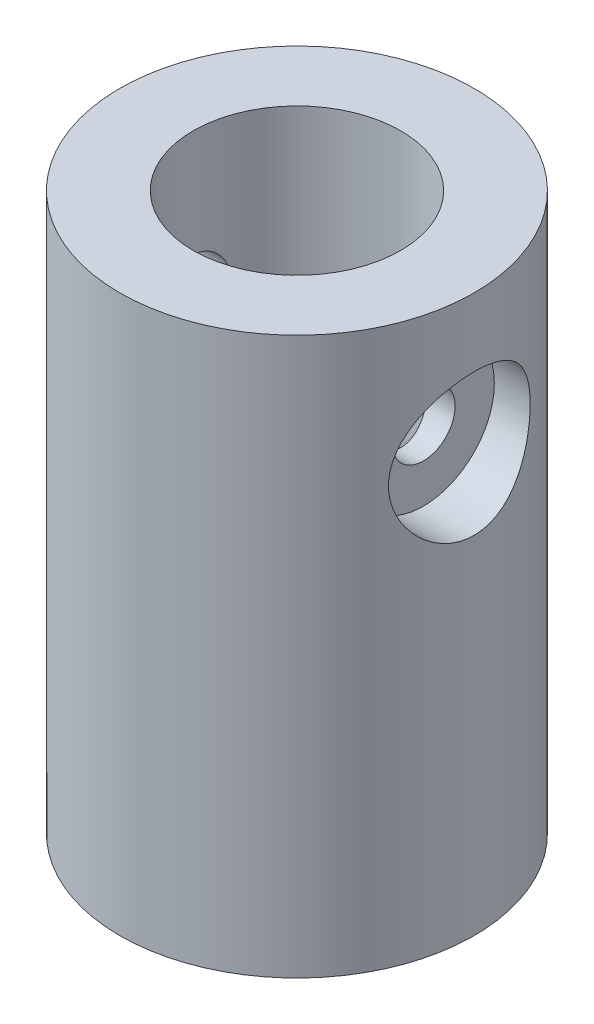
SolidWorks part; units mm, degrees
ref_plane "Front Plane" through (0, 0, 0) normal (0, 0, 1) x (1, 0, 0)
ref_plane "Top Plane" through (0, 0, 0) normal (0, 1, 0) x (1, 0, 0)
ref_plane "Right Plane" through (0, 0, 0) normal (1, 0, 0) x (0, 0, -1)
sketch "Sketch1" plane through (0, 0, 0) normal (0, 1, 0) x (1, 0, 0)
  circle A0 centre (0, 0) radius 7
  dimension "D1" = 14
extrude "Boss-Extrude1" add sketch "Sketch1" along normal blind 22 contours A0
sketch "Sketch2" plane through (0, 22, 0) normal (0, 1, 0) x (1, 0, 0)
  circle A0 centre (0, 0) radius 4.1
  dimension "D1" = 8.2
extrude "Cut-Extrude1" cut sketch "Sketch2" against normal blind 14 contours A0
sketch "Sketch3" plane through (0, 0, 0) normal (0, -1, 0) x (1, 0, 0)
  line L0 (-1.95, 2.0094) -> (-1.95, -2.0094)
  line L1 (1.95, 2.0094) -> (1.95, -2.0094)
  line L2 (0, 0) -> (0, 2.8) construction
  line L3 (0, 0) -> (0, -2.8) construction
  arc A0 (-1.95, -2.0094) -> (1.95, -2.0094) centre (0, 0) ccw
  arc A1 (1.95, 2.0094) -> (-1.95, 2.0094) centre (0, 0) ccw
  dimension "D1" = 5.6
  dimension "D2" = 1.95
  dimension "D3" = 1.95
extrude "Cut-Extrude2" cut sketch "Sketch3" against normal blind 8 contours L0 A0 L1 A1
hole_wizard "CBORE for M5 Hex Head Bolt1" positions "3DSketch1" profile "Sketch4" counterbore size "M5" standard "ANSI Metric" end condition through all
sketch3d "3DSketch1"
  line L0 (0, 22, 0) -> (0, 0, 0) construction
  line L1 (0, 22, 0) -> (0, 0, 0) construction
  line L2 (0, 16.5, 0) -> (7, 16.5, 0) construction
  point P0 (7, 16.5, 0)
  point P17 (7.0592, 14.2085, 0)
  point P18 (7.0592, 16.5, 0)
  dimension "D1" = 5.5
sketch "Sketch4" plane through (7, 16.5, 0) normal (0, 1, 0) x (0, 0, -1)
  line L0 (0, 0) -> (0, 14)
  line L1 (0, 14) -> (1.25, 14)
  line L3 (1.25, 14) -> (1.25, 2)
  line L4 (1.25, 2) -> (2.8, 2)
  line L5 (2.8, 2) -> (2.8, 0)
  line L7 (2.8, 0) -> (0, 0)
  line L11 (0, -6.35) -> (0, 107.95) construction
  dimension "Thru Hole Dia." = 2.5
  dimension "Thru Hole Depth" = 14
  dimension "C'Bore Dia." = 5.6
  dimension "C'Bore Depth" = 2
